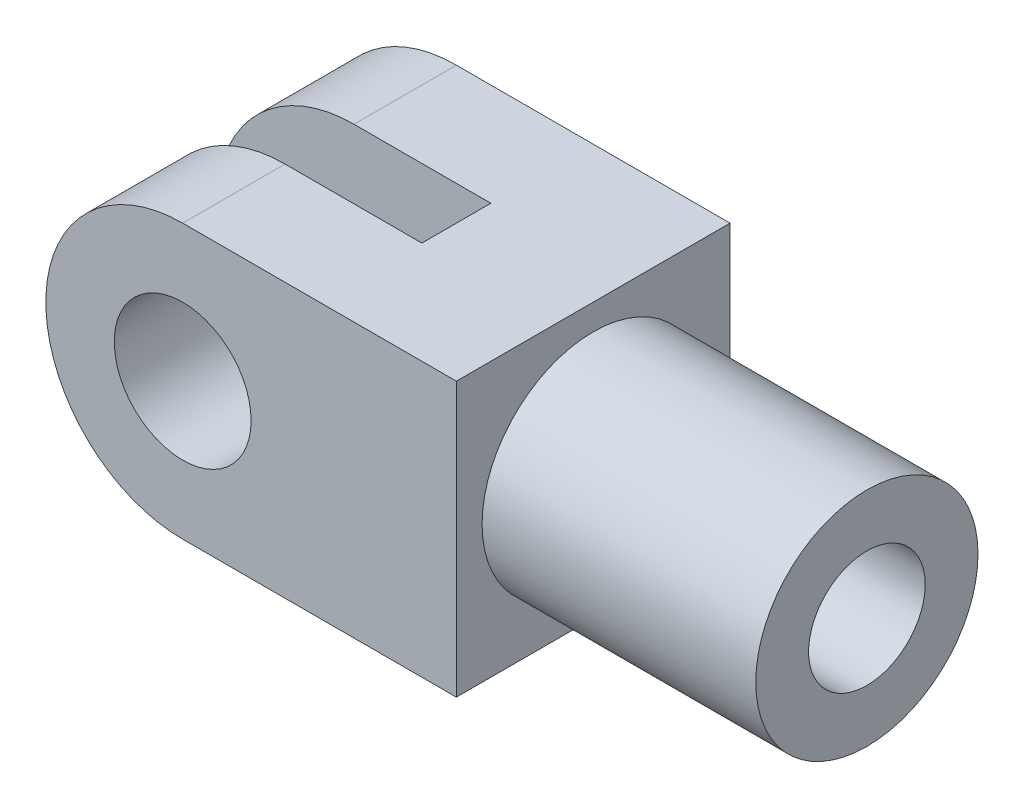
SolidWorks part; units mm, degrees
material "Free-Cutting Brass, UNS C36000"
ref_plane "Front Plane" through (0, 0, 0) normal (0, 0, 1) x (1, 0, 0)
ref_plane "Top Plane" through (0, 0, 0) normal (0, 1, 0) x (1, 0, 0)
ref_plane "Right Plane" through (0, 0, 0) normal (1, 0, 0) x (0, 0, -1)
sketch "Sketch1" plane through (0, 0, 0) normal (0, 0, 1) x (1, 0, 0)
  line L1 (0, 0) -> (-6.35, 0)
  line L2 (0, 0) -> (0, 6.35)
  line L3 (0, 6.35) -> (-6.35, 6.35)
  arc A0 (-6.35, 6.35) -> (-6.35, 0) centre (-6.35, 3.175) ccw
  point P6 (-9.525, 3.175)
  dimension "D2" = 9.525
  dimension "D1" = 6.35
extrude "Boss-Extrude1" add sketch "Sketch1" along normal blind 6.35
sketch "Sketch2" plane through (0, 0, 0) normal (1, 0, 0) x (0, 0, -1)
  line L0 (-3.175, 6.35) -> (-3.175, 0) construction
  line L1 (-6.35, 6.35) -> (0, 6.35) construction
  line L2 (-6.35, 0) -> (0, 0) construction
  circle A0 centre (-3.175, 3.175) radius 2.5781
  dimension "D1" = 5.1562
extrude "Boss-Extrude2" add sketch "Sketch2" along normal blind 6.35
hole_wizard "Tap Drill for #6-32 Tap1" positions "Sketch3" profile "Sketch4" hole size "#6-32" standard "ANSI Inch"
sketch "Sketch3" plane through (6.35, 0, 0) normal (1, 0, 0) x (0, 0, -1)
  point P0 (-3.175, 3.175)
sketch "Sketch4" plane through (6.35, 3.175, 3.175) normal (0, 1, 0) x (0, 0, -1)
  line L0 (0, 0) -> (0, 10.3377)
  line L1 (0, 10.3377) -> (1.3525, 9.525)
  line L2 (1.3525, 9.525) -> (1.3525, 0)
  line L5 (1.3525, 0) -> (0, 0)
  line L10 (0, 10.3377) -> (-1.3526, 9.525) construction
  line L11 (0, -6.35) -> (0, 107.95) construction
  dimension "Hole Dia." = 2.7051
  dimension "Hole Depth" = 9.525
  dimension "Drill Angle" = 118
sketch "Sketch5" plane through (0, 0, 0) normal (0, -1, 0) x (1, 0, 0)
  line L1 (-3.175, 3.9751) -> (-13.335, 3.9751)
  line L2 (-3.175, 3.9751) -> (-3.175, 2.3749)
  line L3 (-3.175, 2.3749) -> (-13.335, 2.3749)
  line L4 (-13.335, 3.9751) -> (-13.335, 2.3749)
  line L5 (-9.525, 6.35) -> (-9.525, 0) construction
  line L6 (0, 6.35) -> (0, 0) construction
  point P8 (0, 3.175)
  point P9 (-3.175, 3.175)
  dimension "D1" = 6.35
  dimension "D2" = 1.6002
  dimension "D3" = 10.16
extrude "Cut-Extrude1" cut sketch "Sketch5" against normal up to next
sketch "Sketch6" plane through (0, 0, 6.35) normal (0, 0, 1) x (1, 0, 0)
  circle A0 centre (-6.35, 3.175) radius 1.5875
  dimension "D1" = 3.175
extrude "Cut-Extrude2" cut sketch "Sketch6" against normal up to next
hole_wizard "#4-40 Tapped Hole1" positions "Sketch7" profile "Sketch8" tap size "#4-40" standard "ANSI Inch" end condition up to next
sketch "Sketch7" plane through (0, 0, 0) normal (0, 0, -1) x (-1, 0, 0)
  point P0 (6.35, 3.175)
sketch "Sketch8" plane through (-6.35, 3.175, 0) normal (1, 0, 0) x (0, 1, 0)
  line L0 (0, 0) -> (0, 2.3749)
  line L1 (0, 2.3749) -> (1.1303, 2.3749)
  line L2 (1.1303, 2.3749) -> (1.1303, 0)
  line L5 (1.1303, 0) -> (0, 0)
  line L11 (0, -6.35) -> (0, 107.95) construction
  dimension "Thru Tap Drill Dia." = 2.2606
  dimension "Thru Tap Drill Depth" = 2.3749
cosmetic thread "Hole Thread1" parameters "D2"=2.8448
